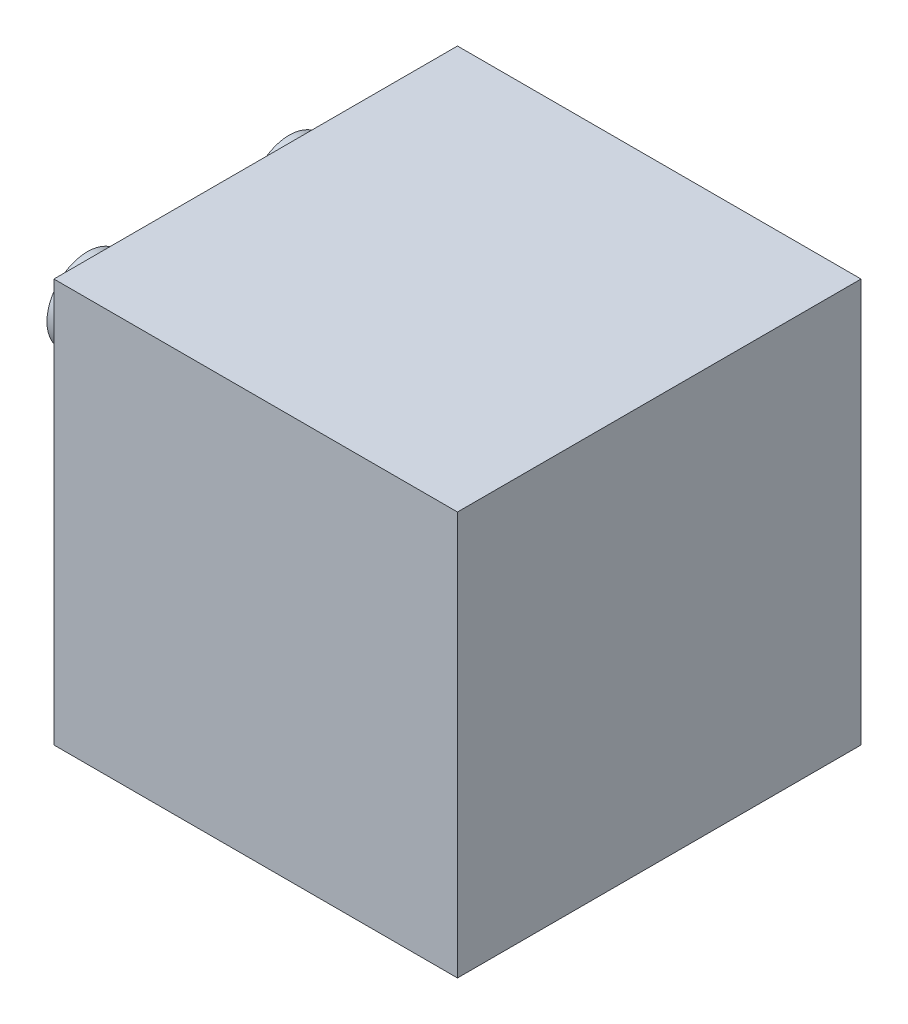
SolidWorks part; units mm, degrees
ref_plane "Front Plane" through (0, 0, 0) normal (0, 0, 1) x (1, 0, 0)
ref_plane "Top Plane" through (0, 0, 0) normal (0, 1, 0) x (1, 0, 0)
ref_plane "Right Plane" through (0, 0, 0) normal (1, 0, 0) x (0, 0, -1)
sketch "Sketch1" plane through (0, 0, 0) normal (0, 1, 0) x (1, 0, 0)
  line L1 (-40.4124, 7.8011) -> (19.4676, 7.8011)
  line L2 (-40.4124, 7.8011) -> (-40.4124, -52.0789)
  line L3 (-40.4124, -52.0789) -> (19.4676, -52.0789)
  line L4 (19.4676, 7.8011) -> (19.4676, -52.0789)
extrude "Boss-Extrude1" add sketch "Sketch1" along normal blind 59.88
sketch "Sketch2" plane through (0, 0, 0) normal (0, -1, 0) x (1, 0, 0)
  line L0 (-10.4724, 7.1689) -> (-10.4724, 2.1689)
  line L1 (-10.4724, -7.8011) -> (-10.4724, 52.0789) construction
  line L2 (19.4676, -7.8011) -> (-40.4124, -7.8011) construction
  line L3 (-40.4124, 52.0789) -> (19.4676, 52.0789) construction
  line L4 (-10.4724, 52.0789) -> (-10.4724, -7.8011) construction
  line L5 (-10.4724, 2.1689) -> (-11.9724, 2.1689)
  line L6 (-10.4724, -7.8011) -> (-10.4724, 22.1389) construction
  line L7 (-10.4724, 7.1689) -> (-10.4724, 12.1689)
  line L8 (-11.9724, 2.1689) -> (-8.9724, 2.1689)
  line L9 (-8.9724, 2.1689) -> (-8.9724, 12.1689)
  line L10 (-8.9724, 12.1689) -> (-11.9724, 12.1689)
  line L11 (-11.9724, 12.1689) -> (-11.9724, 2.1689)
  line L12 (-10.4724, 52.0789) -> (-10.4724, 22.1389) construction
  line L13 (-10.4724, 22.1389) -> (-10.4724, 37.1089) construction
  line L14 (-10.4724, 37.1089) -> (-10.4724, 42.1089) construction
  line L15 (-10.4724, 42.1089) -> (-10.4724, 32.1089) construction
  line L16 (-10.4724, 32.1089) -> (-11.9724, 32.1089)
  line L17 (-11.9724, 32.1089) -> (-11.9724, 42.1089)
  line L18 (-11.9724, 42.1089) -> (-8.9724, 42.1089)
  line L19 (-8.9724, 42.1089) -> (-8.9724, 32.1089)
  line L20 (-8.9724, 32.1089) -> (-10.4724, 32.1089)
extrude "Cut-Extrude1" cut sketch "Sketch2" against normal blind 30 contours L10 L11 L5 L0 L7 | L9 L10 L7 L0 L8 | L20 L19 L18 L17 L16
sketch "Sketch4" plane through (-40.4124, 0, 0) normal (-1, 0, 0) x (0, 0, 1)
  line L0 (-7.8011, 0) -> (-7.8011, 59.88) construction
  line L1 (-7.8011, 59.88) -> (-7.8011, 29.94) construction
  line L2 (-7.8011, 29.94) -> (52.0789, 29.94) construction
  line L3 (52.0789, 59.88) -> (52.0789, 0) construction
  line L4 (52.0789, 29.94) -> (22.1389, 29.94) construction
  line L5 (22.1389, 29.94) -> (-7.8011, 29.94) construction
  line L6 (-7.8011, 29.94) -> (7.1689, 29.94) construction
  line L7 (7.1689, 29.94) -> (7.1689, 59.88) construction
  line L8 (-7.8011, 59.88) -> (52.0789, 59.88) construction
  line L9 (52.0789, 29.94) -> (22.1389, 29.94) construction
  line L10 (22.1389, 29.94) -> (37.1089, 29.94) construction
  line L11 (37.1089, 29.94) -> (37.1089, 59.88) construction
  circle A0 centre (7.1689, 44.91) radius 6
  circle A1 centre (37.1089, 44.91) radius 6
extrude "Boss-Extrude3" add sketch "Sketch4" along normal blind 10
sketch "Sketch5" plane through (-40.4124, 0, 0) normal (-1, 0, 0) x (0, 0, 1)
  line L0 (22.1389, 59.88) -> (22.1389, 0) construction
  line L1 (-7.8011, 59.88) -> (52.0789, 59.88) construction
  line L2 (-7.8011, 0) -> (52.0789, 0) construction
  line L3 (22.1389, 0) -> (22.1389, 29.94) construction
  line L4 (20.1389, 21.94) -> (20.1389, 35.94)
  line L5 (20.1389, 35.94) -> (24.1389, 35.94)
  line L6 (24.1389, 35.94) -> (24.1389, 29.94)
  line L7 (20.1389, 21.94) -> (24.1389, 21.94) construction
  line L8 (24.1389, 21.94) -> (24.1389, 29.94) construction
  line L9 (22.1389, 21.94) -> (22.1389, 0) construction
  line L11 (24.1389, 29.94) -> (24.1389, 21.94)
  line L12 (24.1389, 21.94) -> (20.1389, 21.94)
  line L17 (6.1689, 19.94) -> (6.1689, 9.97) construction
  line L18 (6.1689, 9.97) -> (16.2302, 9.97) construction
  line L19 (16.2302, 9.97) -> (11.1996, 9.97) construction
  line L20 (11.1996, 9.97) -> (11.1996, 20.0957) construction
  line L21 (11.1996, 20.0957) -> (11.1996, 15.0328) construction
  line L30 (41.0819, 15.0328) -> (24.1389, 15.0328) construction
  line L31 (24.1389, 15.0328) -> (32.6104, 15.0328) construction
  line L32 (11.1996, 15.0328) -> (32.6104, 15.0328)
  spline S0 degree 2 poles (11.1996, 15.0328) (22.019, 2.8808) (32.6104, 15.0328) knots 0 0 0 1 1 1
extrude "Boss-Extrude4" add sketch "Sketch5" along normal blind 10
